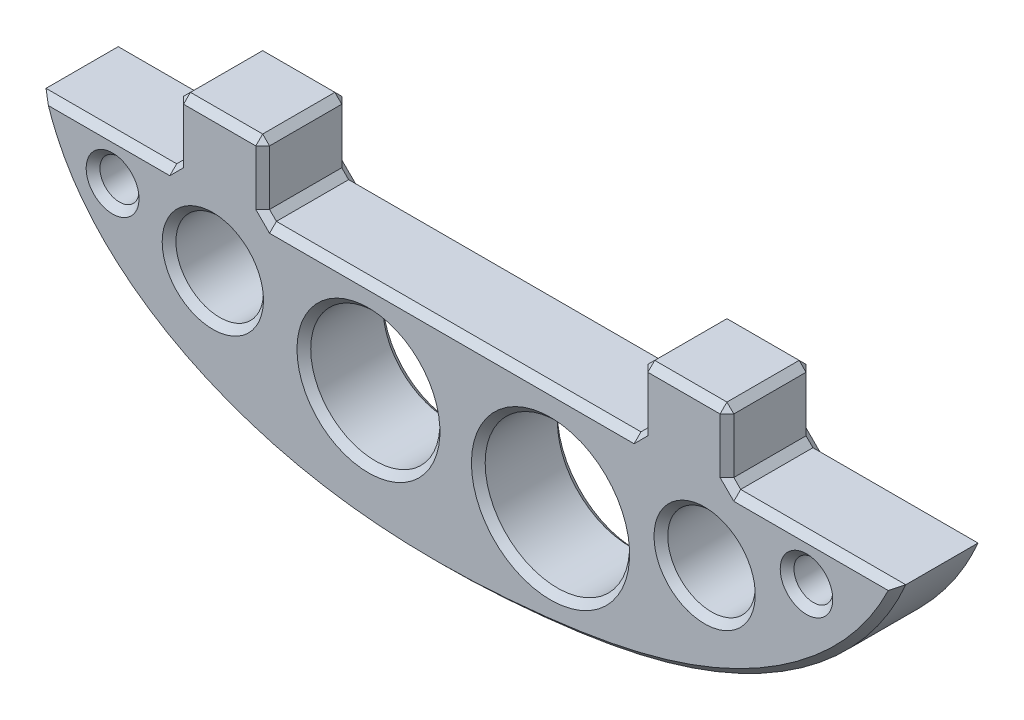
SolidWorks part; units mm, degrees
ref_plane "Ebene vorne" through (0, 0, 0) normal (0, 0, 1) x (1, 0, 0)
ref_plane "Ebene oben" through (0, 0, 0) normal (0, 1, 0) x (1, 0, 0)
ref_plane "Ebene rechts" through (0, 0, 0) normal (1, 0, 0) x (0, 0, -1)
sketch "Skizze1" plane through (0, 0, 0) normal (0, 0, 1) x (1, 0, 0)
  line L0 (-24.9965, 0) -> (25.0035, 0)
  spline S0 degree 3 poles (-24.9965, 0) (-23.4656, -5.4275) (-13.5554, -12.4701) (1.6466, -12.8223) (15.8225, -10.2639) (23.061, -4.556) (25.0035, 0) knots 0 0 0 0 0.271573 0.5678 0.751181 1 1 1 1
  dimension "D1" = 50
extrude "Aufsatz-Linear austragen1" add sketch "Skizze1" along normal blind 5
sketch "Skizze2" plane through (0, 0, 0) normal (0, 1, 0) x (1, 0, 0)
  line L0 (-24.9965, -5) -> (-24.9965, 0) construction
  line L3 (25.0035, 0) -> (-24.9965, 0) construction
  line L4 (-16.9965, 0) -> (-11.9965, 0)
  line L5 (-16.9965, 0) -> (-16.9965, -5)
  line L6 (-16.9965, -5) -> (-11.9965, -5)
  line L7 (-11.9965, 0) -> (-11.9965, -5)
  line L8 (25.0035, -5) -> (-24.9965, -5) construction
  line L9 (25.0035, -5) -> (25.0035, 0) construction
  line L10 (15.0035, 0) -> (10.0035, 0)
  line L11 (15.0035, 0) -> (15.0035, -5)
  line L12 (15.0035, -5) -> (10.0035, -5)
  line L13 (10.0035, 0) -> (10.0035, -5)
  point P18 (-34.4834, 0.3728)
  dimension "D1" = 10
  dimension "D2" = 5
  dimension "D4" = 5
  dimension "D5" = 8
extrude "Aufsatz-Linear austragen2" add sketch "Skizze2" along normal blind 4
sketch "Skizze3" plane through (0, 0, 5) normal (0, 0, 1) x (1, 0, 0)
  circle A0 centre (-14.8956, -3.9447) radius 2.5439
  circle A1 centre (-5.8442, -5.4338) radius 3.7575
  circle A2 centre (4.7429, -6.0975) radius 4.2
  circle A3 centre (13.7063, -4.4756) radius 2.5439
  circle A4 centre (-20.7241, -2.4554) radius 1.1377
  circle A5 centre (19.6303, -2.4554) radius 1.1288
  point P8 (-20.7241, -2.4554)
  point P11 (-14.8956, -3.9447)
  point P12 (-5.8442, -5.4338)
  point P13 (4.7429, -6.0975)
  point P14 (13.7063, -4.4756)
  point P15 (19.6303, -2.4554)
extrude "Schnitt-Linear austragen1" cut sketch "Skizze3" against normal through all
chamfer "Fase1" distance 0.4 angle 45 40 edges at (-19.5864, -2.4554, 0) (-19.5864, -2.4554, 5) (16.2503, -4.4756, 0) (16.2503, -4.4756, 5) (20.7591, -2.4554, 0) (20.7591, -2.4554, 5) (8.9429, -6.0975, 0) (8.9429, -6.0975, 5) (-2.0867, -5.4338, 0) (-2.0867, -5.4338, 5) (-12.3516, -3.9447, 0) (-12.3516, -3.9447, 5) (10.0035, 2, 5) (-16.9965, 2, 5) (15.0035, 2, 0) (10.0035, 2, 0) (12.5035, 4, 5) (10.0035, 4, 2.5) (12.5035, 4, 0) (15.0035, 4, 2.5) (15.0035, 2, 5) (10.0035, 0, 2.5) (15.0035, 0, 2.5) (-11.9965, 0, 2.5) (-16.9965, 4, 2.5) (-14.4965, 4, 5) (-0.9965, 0, 5) (-0.9965, 0, 0) (-11.9965, 2, 5) (-11.9965, 4, 2.5) (-11.9965, 2, 0) (-14.4965, 4, 0) (-16.9965, 2, 0) (20.0035, 0, 5) (20.0035, 0, 0) (-20.9965, 0, 5) (-20.9965, 0, 0) (-16.9965, 0, 2.5)
